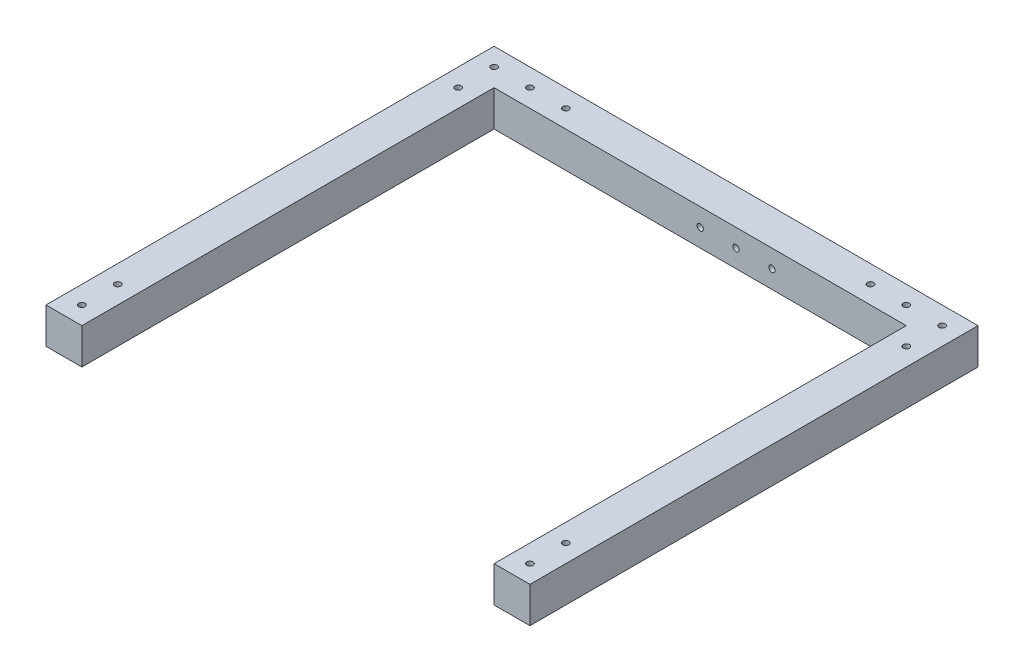
SolidWorks part; units mm, degrees
ref_plane "前视基准面" through (0, 0, 0) normal (0, 0, 1) x (1, 0, 0)
ref_plane "上视基准面" through (0, 0, 0) normal (0, 1, 0) x (1, 0, 0)
ref_plane "右视基准面" through (0, 0, 0) normal (1, 0, 0) x (0, 0, -1)
sketch "草图1" plane through (0, 0, 0) normal (0, 1, 0) x (1, 0, 0)
  line L1 (-135, 10) -> (135, 10)
  line L2 (-135, 10) -> (-135, -10)
  line L3 (-135, -10) -> (135, -10)
  line L4 (135, 10) -> (135, -10)
  line L5 (-135, 10) -> (135, -10) construction
  line L6 (-135, -10) -> (135, 10) construction
  line L7 (-135, -10) -> (-115, -10)
  line L8 (-135, -10) -> (-135, -240)
  line L9 (-135, -240) -> (-115, -240)
  line L10 (-115, -10) -> (-115, -240)
  line L11 (135, -10) -> (115, -10)
  line L12 (135, -10) -> (135, -240)
  line L13 (135, -240) -> (115, -240)
  line L14 (115, -10) -> (115, -240)
  point P0 (0, 0)
  dimension "D1" = 20
  dimension "D2" = 20
  dimension "D3" = 20
  dimension "D4" = 250
  dimension "D5" = 270
extrude "凸台-拉伸1" add sketch "草图1" along normal blind 20 contours L4 L1 L2 L3 | L10 L3 L8 L9 | L3 L14 L13 L12
sketch "草图2" plane through (0, 20, 0) normal (0, 1, 0) x (1, 0, 0)
  line L0 (0, 0) -> (0, -41.9275)
  line L1 (-135, 10) -> (135, 10) construction
  line L2 (-135, -240) -> (-115, -240) construction
  line L4 (-135, 10) -> (-115, 10)
  line L5 (-135, 10) -> (-135, -240)
  line L6 (-135, -240) -> (-115, -240)
  line L7 (-115, 10) -> (-115, -240)
  line L8 (135, 10) -> (115, 10)
  line L9 (135, 10) -> (135, -240)
  line L10 (135, -240) -> (115, -240)
  line L11 (115, 10) -> (115, -240)
  line L12 (-115, 10) -> (115, 10)
  line L13 (-115, 10) -> (-115, -10)
  line L14 (-115, -10) -> (115, -10)
  line L15 (115, 10) -> (115, -10)
  circle A0 centre (-125, -230) radius 1.75
  circle A1 centre (-125, -210) radius 1.75
  circle A2 centre (-125, -20) radius 1.75
  circle A3 centre (-125, 0) radius 1.75
  circle A4 centre (-105, 0) radius 1.75
  circle A5 centre (-85, 0) radius 1.75
  circle A6 centre (125, -230) radius 1.75
  circle A7 centre (125, -210) radius 1.75
  circle A8 centre (125, -20) radius 1.75
  circle A9 centre (125, 0) radius 1.75
  circle A10 centre (105, 0) radius 1.75
  circle A11 centre (85, 0) radius 1.75
  dimension "D1" = 10
  dimension "D7" = 3.5
  dimension "D2" = 20
  dimension "D3" = 20
  dimension "D4" = 20
  dimension "D5" = 20
  dimension "D6" = 10
  dimension "D8" = 10
extrude "切除-拉伸1" cut sketch "草图2" against normal up to next contours A3 | A2 | A4 | A1 | A0 | A7 | A6 | A9 | A8 | A10 | A11 | A5
sketch "草图3" plane through (0, 0, -10) normal (0, 0, -1) x (-1, 0, 0)
  line L0 (135, 0) -> (-135, 0) construction
  circle A0 centre (-20, 10) radius 1.75
  circle A1 centre (0, 10) radius 1.75
  circle A2 centre (-40, 10) radius 1.75
  point P6 (0, 0)
  point P9 (0, 0)
  point P11 (-35.573, 5.9696)
  dimension "D1" = 10
  dimension "D4" = 3.5
  dimension "D2" = 20
  dimension "D3" = 20
extrude "切除-拉伸2" cut sketch "草图3" against normal up to next
